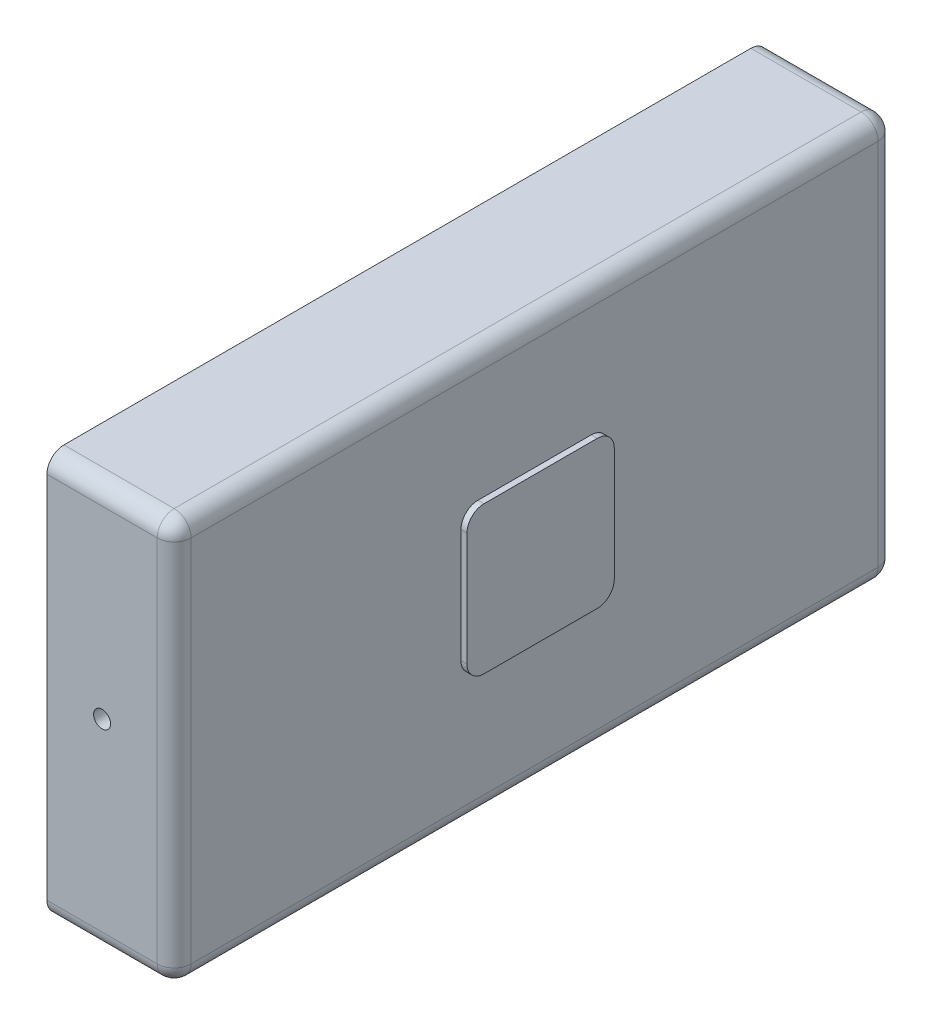
SolidWorks part; units mm, degrees
material "FOXTECH"
ref_plane "Front Plane" through (0, 0, 0) normal (0, 0, 1) x (1, 0, 0)
ref_plane "Top Plane" through (0, 0, 0) normal (0, 1, 0) x (1, 0, 0)
ref_plane "Right Plane" through (0, 0, 0) normal (1, 0, 0) x (0, 0, -1)
sketch "Sketch1" plane through (-20.2909, 0, 0) normal (1, 0, 0) x (0, 0, -1)
  line L1 (-97.812, 26.8071) -> (10.138, 26.8071)
  line L2 (-97.812, 26.8071) -> (-97.812, -33.5179)
  line L3 (-97.812, -33.5179) -> (10.138, -33.5179)
  line L4 (10.138, 26.8071) -> (10.138, -33.5179)
  dimension "D1" = 107.95
  dimension "D2" = 60.325
extrude "Boss-Extrude1" add sketch "Sketch1" along normal blind 19.05
sketch "Sketch2" plane through (-1.2409, 0, 0) normal (1, 0, 0) x (0, 0, -1)
  line L0 (-43.837, 26.8071) -> (-43.837, -33.5179) construction
  line L1 (10.138, 26.8071) -> (-97.812, 26.8071) construction
  line L2 (-97.812, -33.5179) -> (10.138, -33.5179) construction
  line L4 (-97.812, 26.8071) -> (-97.812, -33.5179) construction
  line L5 (-97.812, -3.3554) -> (10.138, -3.3554) construction
  line L6 (10.138, -33.5179) -> (10.138, 26.8071) construction
  circle A0 centre (-43.837, -3.3554) radius 7.62
  dimension "D1" = 15.24
fillet "Fillet1" radius 2.54 8 edges at (-1.2409, -3.3554, -10.138) (-1.2409, -33.5179, 43.837) (-1.2409, -3.3554, 97.812) (-1.2409, 26.8071, 43.837) (-10.7659, -33.5179, 97.812) (-10.7659, -33.5179, -10.138) (-10.7659, 26.8071, 97.812) (-10.7659, 26.8071, -10.138)
sketch "Sketch5" plane through (0, 0, -10.138) normal (0, 0, -1) x (-1, 0, 0)
  line L0 (3.7809, -3.3554) -> (20.2909, -3.3554) construction
  line L1 (3.7809, 24.2671) -> (3.7809, -30.9779) construction
  line L2 (20.2909, -30.9779) -> (20.2909, 24.2671) construction
  circle A0 centre (12.0359, -3.3554) radius 1.27
  dimension "D1" = 2.54
extrude "Cut-Extrude2" cut sketch "Sketch5" against normal blind 2.54
sketch "Sketch6" plane through (0, 0, 97.812) normal (0, 0, 1) x (1, 0, 0)
  line L0 (-3.7809, -3.3554) -> (-20.2909, -3.3554) construction
  line L1 (-3.7809, -30.9779) -> (-3.7809, 24.2671) construction
  line L2 (-20.2909, 24.2671) -> (-20.2909, -30.9779) construction
  circle A0 centre (-12.0359, -3.3554) radius 1.27
  dimension "D1" = 2.54
extrude "Cut-Extrude3" cut sketch "Sketch6" against normal blind 2.54
sketch "Sketch7" plane through (-1.2409, 0, 0) normal (1, 0, 0) x (0, 0, -1)
  line L0 (-43.837, 7.6745) -> (-43.837, -14.3854) construction
  line L1 (-52.3282, 7.6745) -> (-35.3458, 7.6745)
  line L2 (-54.8682, 5.1345) -> (-54.8682, -11.8454)
  line L3 (-52.3282, -14.3854) -> (-35.3458, -14.3854)
  line L4 (-32.8058, 5.1345) -> (-32.8058, -11.8454)
  line L5 (-54.8682, -3.3554) -> (-32.8058, -3.3554) construction
  line L6 (-97.812, -30.9779) -> (-97.812, 24.2671) construction
  line L7 (10.138, 24.2671) -> (10.138, -30.9779) construction
  line L8 (-95.272, 26.8071) -> (7.598, 26.8071) construction
  line L9 (7.598, -33.5179) -> (-95.272, -33.5179) construction
  arc A0 (-35.3458, -14.3854) -> (-32.8058, -11.8454) centre (-35.3458, -11.8454) ccw
  arc A1 (-54.8682, -11.8454) -> (-52.3282, -14.3854) centre (-52.3282, -11.8454) ccw
  arc A2 (-35.3458, 7.6745) -> (-32.8058, 5.1345) centre (-35.3458, 5.1345) cw
  arc A3 (-52.3282, 7.6745) -> (-54.8682, 5.1345) centre (-52.3282, 5.1345) ccw
  dimension "D3" = 2.54
  dimension "D1" = 22.0624
  dimension "D2" = 22.0599
extrude "Boss-Extrude3" add sketch "Sketch7" along normal blind 0.9017
sketch "Sketch8" plane through (-20.2909, 0, 0) normal (-1, 0, 0) x (0, 0, 1)
  line L0 (-7.598, 26.8071) -> (95.272, 26.8071) construction
  line L1 (97.812, 24.2671) -> (97.812, -30.9779) construction
  circle A0 centre (88.541, 21.2814) radius 1.016
  dimension "D2" = 9.271
  dimension "D3" = 2.032
  dimension "D1" = 5.5257
extrude "Boss-Extrude4" add sketch "Sketch8" along normal blind 3.048
sketch "Sketch9" plane through (-20.2909, 0, 0) normal (-1, 0, 0) x (0, 0, 1)
  line L1 (88.3676, -28.7591) -> (96.3051, -28.7591)
  line L2 (88.3676, -28.7591) -> (88.3676, -32.8231)
  line L3 (88.3676, -32.8231) -> (96.3051, -32.8231)
  line L4 (96.3051, -28.7591) -> (96.3051, -32.8231)
  dimension "D1" = 7.9375
  dimension "D2" = 4.064
extrude "Cut-Extrude4" cut sketch "Sketch9" against normal blind 4.064
sketch "Sketch10" plane through (-16.2269, 0, 0) normal (-1, 0, 0) x (0, 0, 1)
  line L0 (88.8689, -28.9084) -> (88.8689, -32.3233)
  line L1 (88.8689, -32.3233) -> (95.6804, -32.3233)
  line L2 (95.6804, -32.3233) -> (95.6804, -28.9084)
  line L3 (96.0134, -28.9084) -> (96.0134, -32.6483)
  line L4 (96.0134, -32.6483) -> (88.5182, -32.6483)
  line L5 (88.5182, -32.6483) -> (88.5182, -28.9084)
  line L6 (88.5182, -28.9084) -> (88.8689, -28.9084)
  line L7 (95.6804, -28.9084) -> (96.0134, -28.9084)
extrude "Boss-Extrude5" add sketch "Sketch10" along normal blind 5.334
